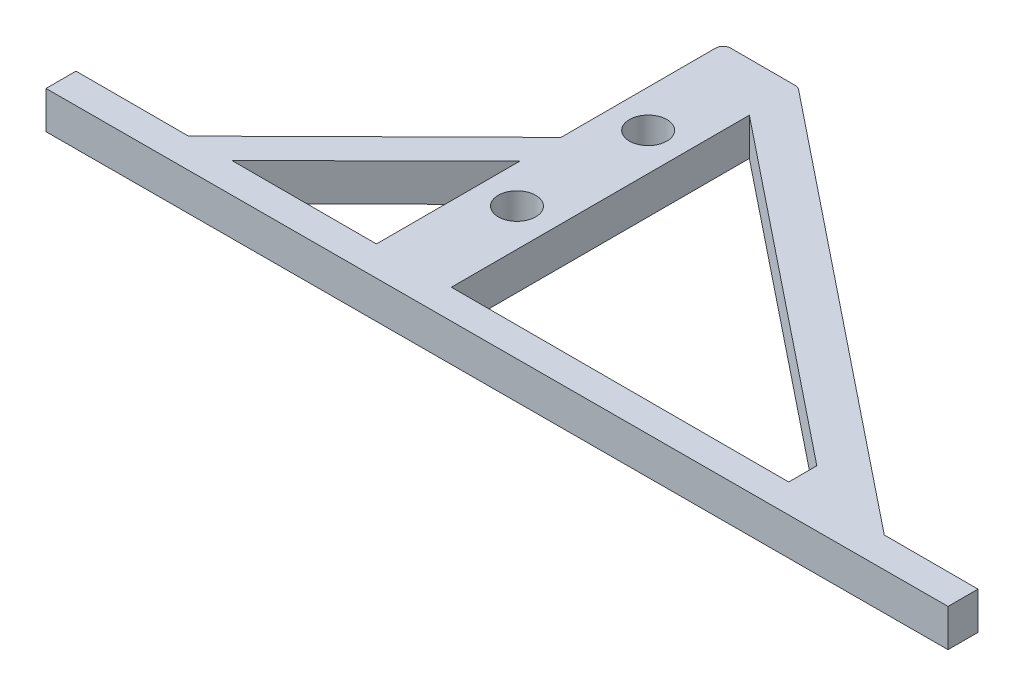
SolidWorks part; units mm, degrees
ref_plane "Front Plane" through (0, 0, 0) normal (0, 0, 1) x (1, 0, 0)
ref_plane "Top Plane" through (0, 0, 0) normal (0, 1, 0) x (1, 0, 0)
ref_plane "Right Plane" through (0, 0, 0) normal (1, 0, 0) x (0, 0, -1)
sketch "Sketch1" plane through (0, 0, 0) normal (0, 1, 0) x (1, 0, 0)
  line L1 (0, 9.525) -> (0, 58.085)
  line L2 (25.4, 9.525) -> (25.4, 110.49)
  line L4 (139.7, 9.525) -> (139.7, 19.05)
  line L6 (171.45, 10.16) -> (26.0957, 126.4434)
  line L7 (139.7, 19.05) -> (25.4, 110.49)
  line L8 (-48.962, 9.525) -> (0, 58.085)
  line L10 (-63.5, 9.3329) -> (0, 72.055)
  line L11 (0, 72.055) -> (0, 124.46)
  line L12 (-63.5, 9.3329) -> (-101.6, 9.3329)
  line L13 (-101.6, 9.3329) -> (-101.6, -0.8271)
  line L15 (2.54, 127) -> (24.509, 127)
  line L17 (203.2, 0) -> (203.2, 10.16)
  line L18 (203.2, 10.16) -> (171.45, 10.16)
  line L20 (139.7, 9.525) -> (25.4, 9.525)
  line L21 (0, 9.525) -> (-48.962, 9.525)
  line L22 (-101.6, -0.8271) -> (203.2, 0)
  circle A0 centre (12.7, 88.9) radius 6.35
  arc A2 (26.0957, 126.4434) -> (24.509, 127) centre (24.509, 124.46) ccw
  arc A3 (0, 124.46) -> (2.54, 127) centre (2.54, 124.46) cw
  circle A4 centre (12.7, 44.45) radius 6.35
  point P3 (26.1668, 200.9321)
  point P20 (25.4, 127)
  point P24 (0, 127)
  dimension "D4" = 12.7
  dimension "D7" = 2.54
  dimension "D2" = 12.7
  dimension "D3" = 44.45
  dimension "D6" = 12.7
  dimension "D8" = 304.8
  dimension "D9" = 10.16
  dimension "D12" = 10.16
  dimension "D14" = 13.97
  dimension "D15" = 38.1
extrude "Boss-Extrude1" add sketch "Sketch1" along normal blind 12.7
